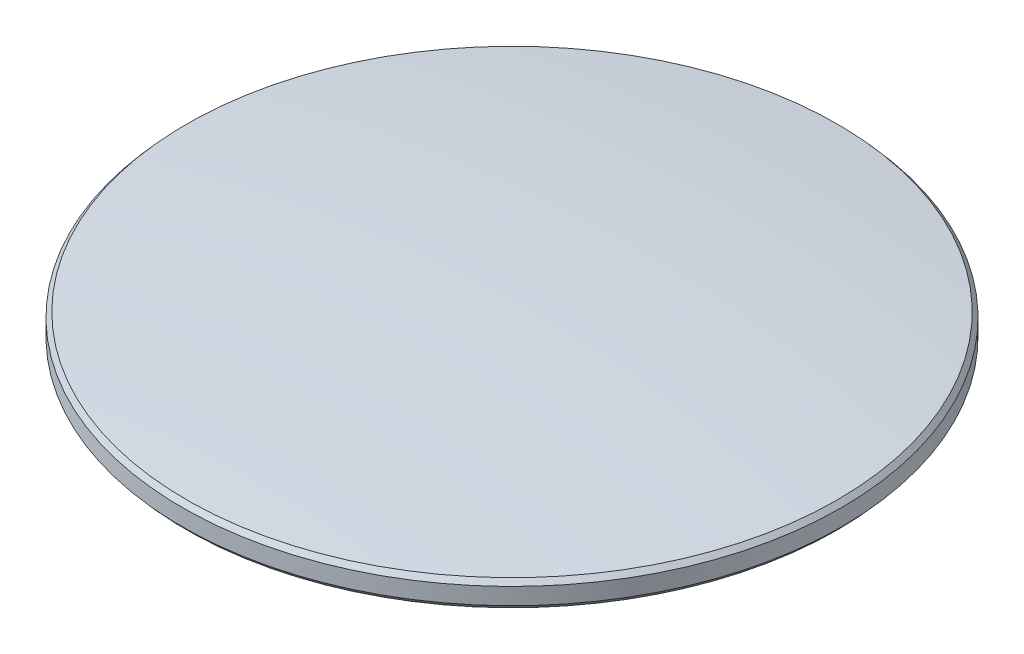
SolidWorks part; units mm, degrees
ref_plane "Plan de face" through (0, 0, 0) normal (0, 0, 1) x (1, 0, 0)
ref_plane "Plan de dessus" through (0, 0, 0) normal (0, 1, 0) x (1, 0, 0)
ref_plane "Plan de droite" through (0, 0, 0) normal (1, 0, 0) x (0, 0, -1)
sketch "Esquisse1" plane through (0, 0, 0) normal (0, 0, 1) x (1, 0, 0)
  line L0 (0, 0) -> (0, 4)
  line L2 (-39.5, 1.5) -> (-39.5, 0)
  line L3 (-39.5, 0) -> (0, 0)
  arc A0 (0, 4) -> (-39.5, 1.5) centre (0, -309.3) ccw
  dimension "D2" = 4
  dimension "D1" = 39.5
  dimension "D3" = 1.5
revolve "Révolution1" add sketch "Esquisse1" angle 360 about L0
chamfer "Chanfrein1" distance 0.5 distance2 0.5 1 edges at (39.5, 1.5, 0)
mirror "Symétrie1" about plane through (-39.5, 0, 0) normal (0, 1, 0) of "Chanfrein1", "Révolution1"
